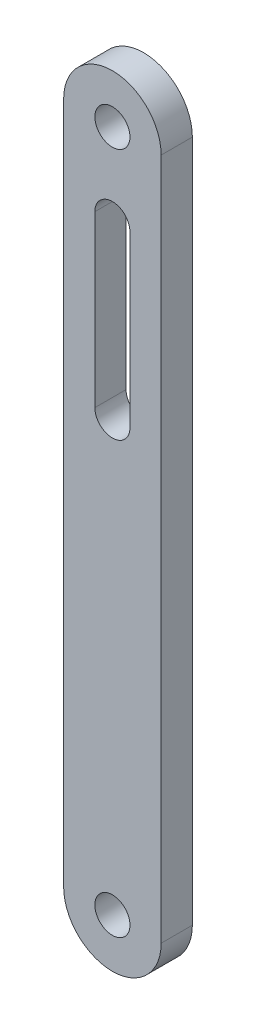
SolidWorks part; units mm, degrees
ref_plane "Front Plane" through (0, 0, 0) normal (0, 0, 1) x (1, 0, 0)
ref_plane "Top Plane" through (0, 0, 0) normal (0, 1, 0) x (1, 0, 0)
ref_plane "Right Plane" through (0, 0, 0) normal (1, 0, 0) x (0, 0, -1)
sketch "Sketch1" plane through (0, 0, 0) normal (0, 0, 1) x (1, 0, 0)
  line L0 (0, -35) -> (0, 35) construction
  line L5 (-5, -35) -> (-5, 35)
  line L6 (5, -35) -> (5, 35)
  line L8 (0, 26.5744) -> (0, 9.1706) construction
  line L9 (1.8, 26.5744) -> (1.8, 9.1706)
  line L10 (-1.8, 26.5744) -> (-1.8, 9.1706)
  circle A0 centre (0, 35) radius 1.8
  circle A1 centre (0, -35) radius 1.8
  arc A2 (1.8, 26.5744) -> (-1.8, 26.5744) centre (0, 26.5744) ccw
  arc A3 (-1.8, 9.1706) -> (1.8, 9.1706) centre (0, 9.1706) ccw
  arc A4 (-5, -35) -> (5, -35) centre (0, -35) ccw
  arc A5 (5, 35) -> (-5, 35) centre (0, 35) ccw
  point P0 (0, 0)
  point P2 (0, 0)
  point P11 (0, 37.85)
  point P13 (0, 0)
  point P16 (0, 17.8725)
  point P21 (0, -35)
  point P22 (-1.8, 26.5744)
  point P23 (0, 0)
  dimension "D3" = 3.6
  dimension "D5" = 3.6
  dimension "D1" = 3.2
  dimension "D6" = 5
  dimension "D7" = 17.8725
  dimension "D2" = 17.4038
  dimension "D4" = 35
extrude "Boss-Extrude1" add sketch "Sketch1" along normal blind 3.2
